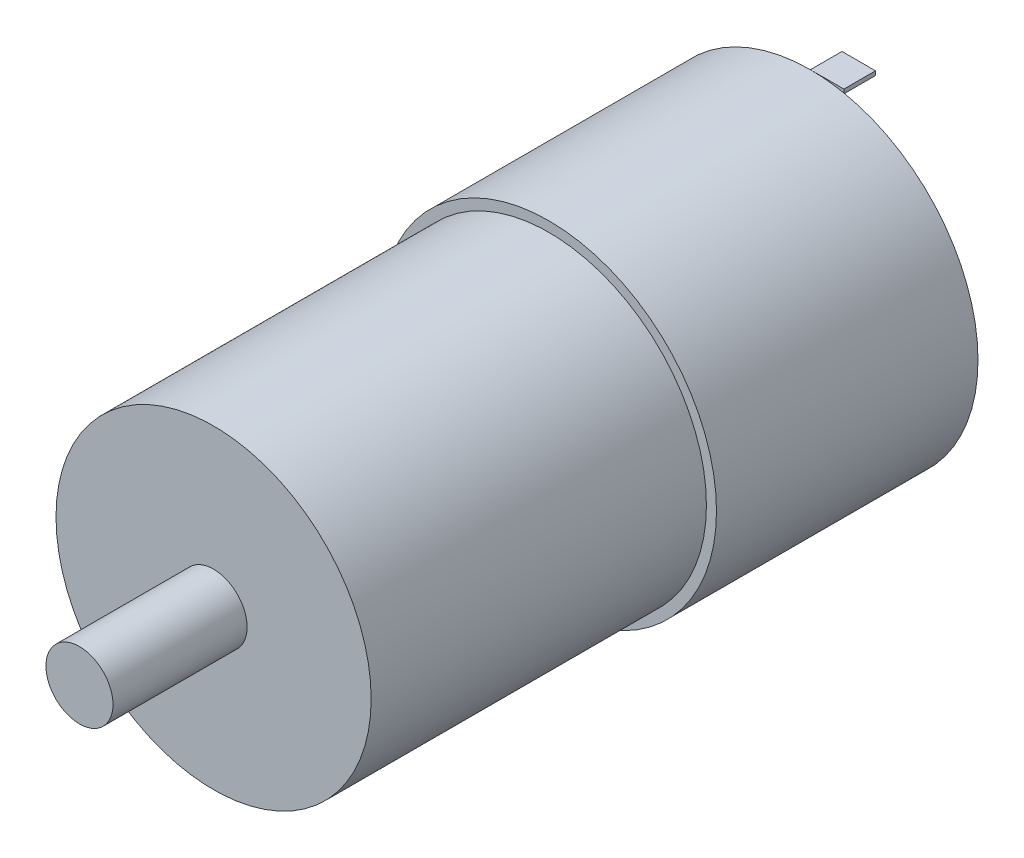
SolidWorks part; units mm, degrees
ref_plane "Front Plane" through (0, 0, 0) normal (0, 0, 1) x (1, 0, 0)
ref_plane "Top Plane" through (0, 0, 0) normal (0, 1, 0) x (1, 0, 0)
ref_plane "Right Plane" through (0, 0, 0) normal (1, 0, 0) x (0, 0, -1)
sketch "Sketch1" plane through (0, 0, 0) normal (0, 0, 1) x (1, 0, 0)
  circle A0 centre (0, 0) radius 25
extrude "Boss-Extrude1" add sketch "Sketch1" along normal blind 39
sketch "Sketch2" plane through (0, 0, 39) normal (0, 0, 1) x (1, 0, 0)
  circle A0 centre (0, 0) radius 23.5
extrude "Boss-Extrude2" add sketch "Sketch2" along normal blind 50
sketch "Sketch3" plane through (0, 0, 89) normal (0, 0, 1) x (1, 0, 0)
  circle A0 centre (0, 0) radius 5
extrude "Boss-Extrude3" add sketch "Sketch3" along normal blind 20 contours A0
sketch "Sketch4" plane through (0, 0, 0) normal (1, 0, 0) x (0, 0, -1)
  line L0 (0, -25) -> (0, 25) construction
  line L1 (0, 24.3848) -> (4.7179, 24.3848)
  line L2 (0, 24.3848) -> (0, 25)
  line L3 (0, 25) -> (4.7179, 25)
  line L4 (4.7179, 24.3848) -> (4.7179, 25)
  line L6 (0, -24.1791) -> (4.7179, -24.1791)
  line L7 (0, -24.1791) -> (0, -25.5183)
  line L8 (0, -25.5183) -> (4.7179, -25.5183)
  line L9 (4.7179, -24.1791) -> (4.7179, -25.5183)
extrude "Boss-Extrude4" add sketch "Sketch4" along normal blind 5
